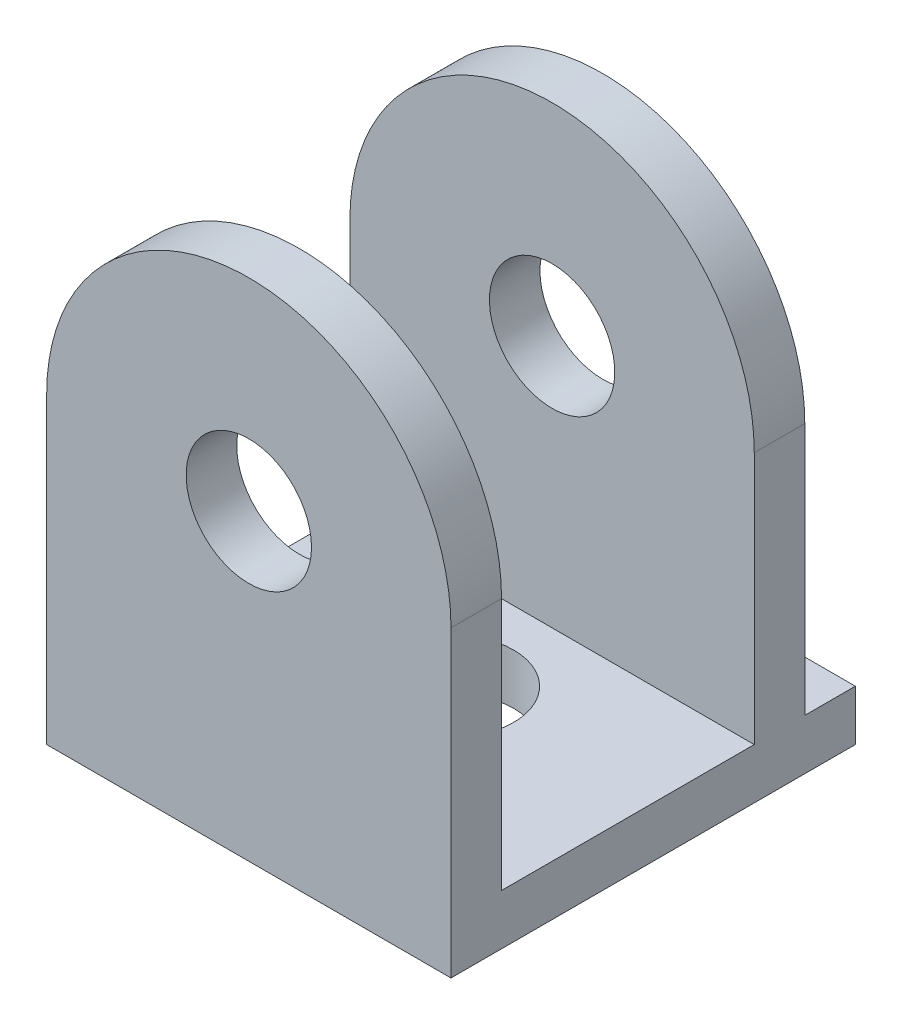
SolidWorks part; units mm, degrees
ref_plane "Front Plane" through (0, 0, 0) normal (0, 0, 1) x (1, 0, 0)
ref_plane "Top Plane" through (0, 0, 0) normal (0, 1, 0) x (1, 0, 0)
ref_plane "Right Plane" through (0, 0, 0) normal (1, 0, 0) x (0, 0, -1)
sketch "Sketch1" plane through (0, 0, 0) normal (0, 0, 1) x (1, 0, 0)
  line L0 (0, 0) -> (0, 41.3703) construction
  line L2 (-10, 15) -> (10, 15)
  line L3 (-10, 15) -> (-10, 0)
  line L4 (-10, 0) -> (10, 0)
  line L5 (10, 15) -> (10, 0)
  line L6 (-10, 15) -> (10, 0) construction
  line L7 (-10, 0) -> (10, 15) construction
  arc A0 (-10, 15) -> (10, 15) centre (0, 15) cw
  point P3 (0, 7.5)
  dimension "D1" = 15
  dimension "D2" = 20
extrude "Boss-Extrude1" add sketch "Sketch1" along normal mid plane 20 contours A0 L2 | L5 L2 L3 L4
sketch "Sketch2" plane through (0, 0, 0) normal (1, 0, 0) x (0, 0, -1)
  line L0 (-10, 0) -> (10, 0) construction
  line L1 (-7.5, 25) -> (5, 25)
  line L2 (-7.5, 25) -> (-7.5, 2.5)
  line L3 (-7.5, 2.5) -> (5, 2.5)
  line L4 (5, 25) -> (5, 2.5)
  line L5 (10, 25) -> (7.5, 25)
  line L6 (10, 25) -> (10, 2.5)
  line L7 (10, 2.5) -> (7.5, 2.5)
  line L8 (7.5, 25) -> (7.5, 2.5)
  line L9 (10, 25) -> (-10, 25) construction
  line L10 (-10, 25) -> (-10, 15) construction
  dimension "D1" = 2.5
  dimension "D2" = 2.5
  dimension "D3" = 2.5
  dimension "D4" = 2.5
  dimension "D5" = 2.5
extrude "Cut-Extrude1" cut sketch "Sketch2" against normal through all both and the other way through all
sketch "Sketch3" plane through (0, 0, 10) normal (0, 0, 1) x (1, 0, 0)
  arc A0 (10, 15) -> (-10, 15) centre (0, 15) ccw construction
  arc A1 (10, 15) -> (-10, 15) centre (0, 15) ccw
  circle A2 centre (0, 15) radius 3.1
  dimension "D1" = 6.2
extrude "Cut-Extrude2" cut sketch "Sketch3" against normal through all and the other way through all contours A2
sketch "Sketch4" plane through (0, 0, 0) normal (0, -1, 0) x (1, 0, 0)
  circle A0 centre (0, 0) radius 3.1
  dimension "D1" = 6.2
extrude "Cut-Extrude3" cut sketch "Sketch4" against normal through all
